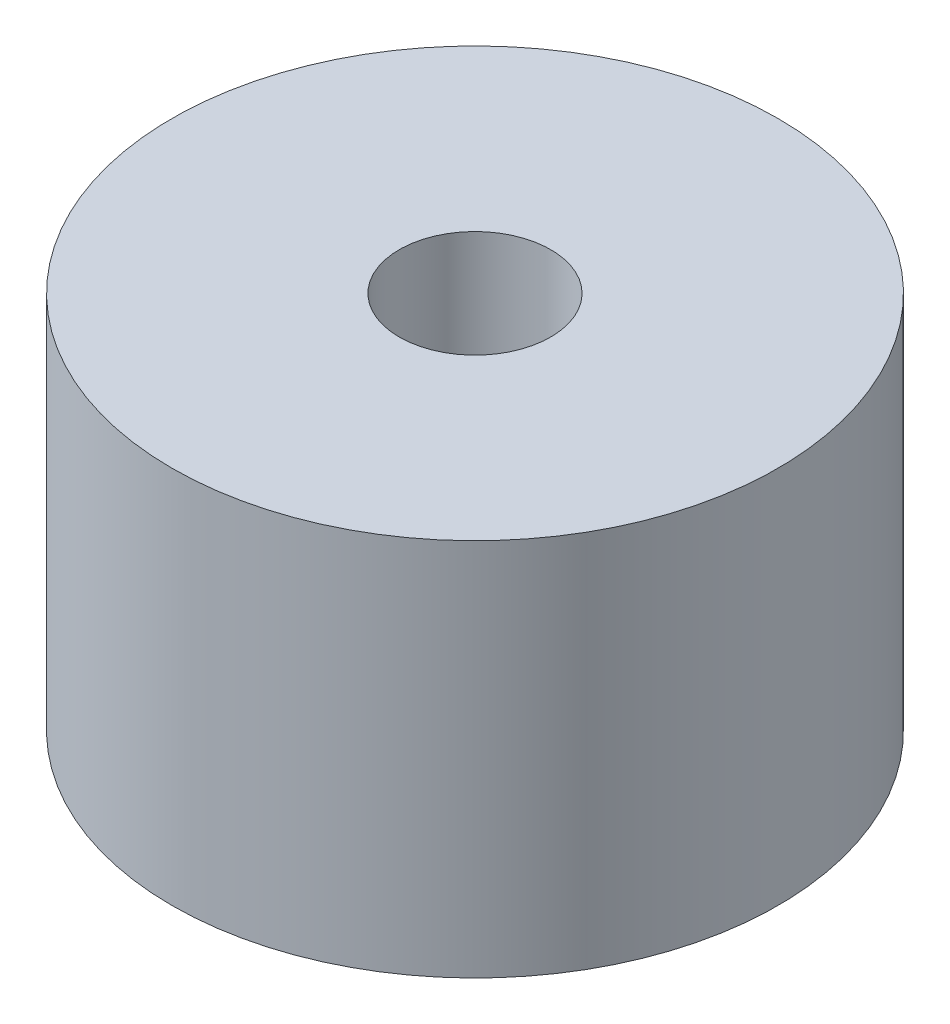
SolidWorks part; units mm, degrees
ref_plane "Front Plane" through (0, 0, 0) normal (0, 0, 1) x (1, 0, 0)
ref_plane "Top Plane" through (0, 0, 0) normal (0, 1, 0) x (1, 0, 0)
ref_plane "Right Plane" through (0, 0, 0) normal (1, 0, 0) x (0, 0, -1)
sketch "Sketch1" plane through (0, 0, 0) normal (0, 1, 0) x (1, 0, 0)
  circle A0 centre (0, 0) radius 4
  dimension "D1" = 8
extrude "Boss-Extrude1" add sketch "Sketch1" along normal blind 5
sketch "Sketch2" plane through (0, 5, 0) normal (0, 1, 0) x (1, 0, 0)
  circle A0 centre (0, 0) radius 1
  dimension "D1" = 2
extrude "Cut-Extrude1" cut sketch "Sketch2" against normal blind 5
